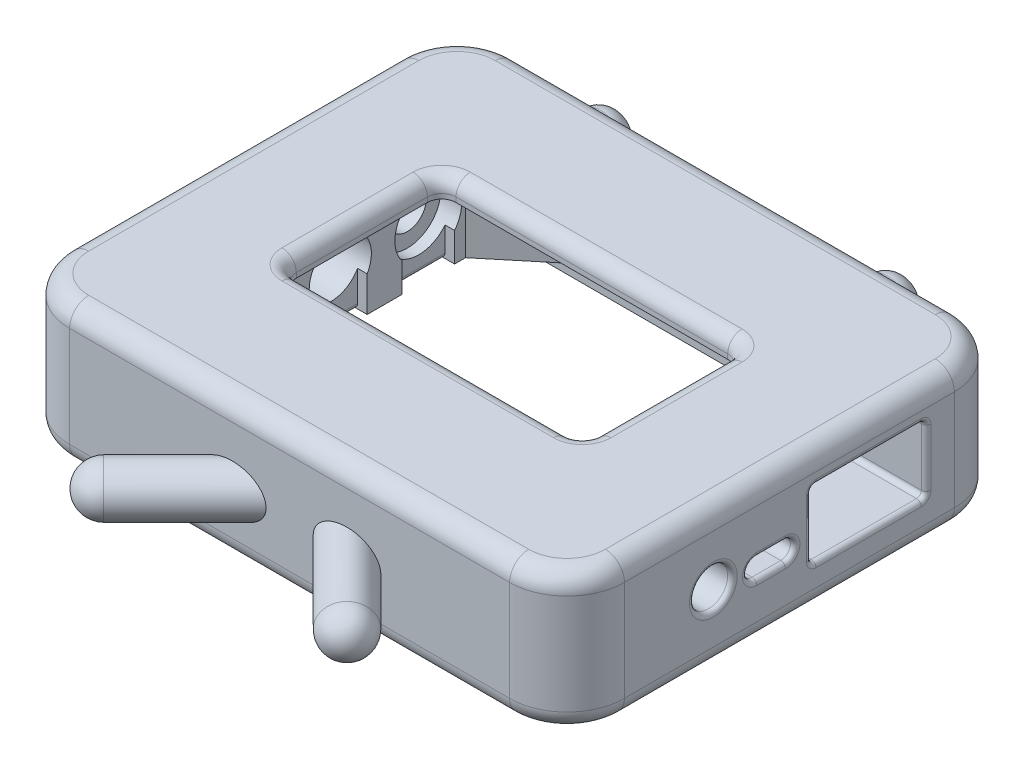
SolidWorks part; units mm, degrees
ref_plane "前视基准面" through (0, 0, 0) normal (0, 0, 1) x (1, 0, 0)
ref_plane "上视基准面" through (0, 0, 0) normal (0, 1, 0) x (1, 0, 0)
ref_plane "右视基准面" through (0, 0, 0) normal (1, 0, 0) x (0, 0, -1)
sketch "草图1" plane through (0, 0, 0) normal (0, 1, 0) x (1, 0, 0)
  line L0 (0, -23.25) -> (0, 24.5) construction
  line L7 (-29, 23.25) -> (29, 23.25)
  line L8 (-29, 23.25) -> (-29, -23.25)
  line L9 (-29, -23.25) -> (29, -23.25)
  line L10 (29, 23.25) -> (29, -23.25)
  line L11 (-29, 23.25) -> (29, -23.25) construction
  line L12 (-29, -23.25) -> (29, 23.25) construction
  line L13 (-29, 23.25) -> (29, 23.25) construction
  line L20 (-19.2, -17.25) -> (19.2, -17.25)
  line L21 (-19.2, -17.25) -> (-19.2, 20.15)
  line L22 (-19.2, 20.15) -> (19.2, 20.15)
  line L23 (19.2, -17.25) -> (19.2, 20.15)
  line L24 (-19.2, -17.25) -> (19.2, 20.15) construction
  line L25 (-19.2, 20.15) -> (19.2, -17.25) construction
  point P0 (0, 0)
  point P3 (0, 1.45)
  point P6 (0, 0)
  dimension "D1" = 58
  dimension "D2" = 46.5
  dimension "D3" = 6
  dimension "D4" = 38.4
  dimension "D5" = 37.4
  dimension "D6" = 3.1
extrude "凸台-拉伸1" add sketch "草图1" along normal blind 12.5
sketch "草图2" plane through (0, 12.5, 0) normal (0, 1, 0) x (1, 0, 0)
  line L13 (15.7, -8.35) -> (-15.7, -8.35)
  line L18 (15.7, -8.35) -> (15.7, 8.35)
  line L19 (15.7, 8.35) -> (-15.7, 8.35)
  line L20 (-15.7, -8.35) -> (-15.7, 8.35)
  line L25 (15.7, -8.35) -> (-15.7, 8.35) construction
  line L39 (15.7, 8.35) -> (-15.7, -8.35) construction
  line L40 (29, -23.25) -> (-29, -23.25)
  line L41 (29, -23.25) -> (29, 23.25)
  line L42 (29, 23.25) -> (-29, 23.25)
  line L43 (-29, -23.25) -> (-29, 23.25)
  line L44 (29, -23.25) -> (-29, 23.25) construction
  line L45 (29, 23.25) -> (-29, -23.25) construction
  point P0 (0, 0)
  point P4 (0, 0)
  dimension "D1" = 31.4
  dimension "D2" = 16.7
extrude "凸台-拉伸2" add sketch "草图2" along normal blind 2
fillet "圆角1" radius 6 4 edges at (29, 7.25, 23.25) (29, 7.25, -23.25) (-29, 7.25, -23.25) (-29, 7.25, 23.25)
sketch "草图11" plane through (0, 0, 23.25) normal (0, 0, 1) x (1, 0, 0)
  line L0 (0, 14.5) -> (0, 0)
  line L2 (-6, 13) -> (-6, 0) construction
  line L3 (-23, 0) -> (23, 0) construction
  line L4 (6, 13) -> (6, 0) construction
  line L6 (-23, 14.5) -> (23, 14.5) construction
  dimension "D1" = 6
  dimension "D2" = 6
ref_plane "left" through (14.625, 0, 14.625) normal (0.7071, 0, 0.7071) x (0, -1, 0)
ref_plane "right" through (-14.625, 0, 14.625) normal (-0.7071, 0, 0.7071) x (0, -1, 0)
sketch "草图8" plane through (-14.625, 0, 14.625) normal (-0.7071, 0, 0.7071) x (0, -1, 0)
  line L0 (-13, 12.1976) -> (0, 12.1976) construction
  circle A0 centre (-6.5, 12.1976) radius 2.5
  dimension "D1" = 5
extrude "凸台-拉伸3" add sketch "草图8" along normal blind 12 and the other way blind 3
sketch "草图9" plane through (14.625, 0, 14.625) normal (0.7071, 0, 0.7071) x (0, -1, 0)
  line L0 (-13, -12.1976) -> (0, -12.1976) construction
  circle A0 centre (-6.5, -12.1976) radius 2.5
  dimension "D1" = 5
extrude "凸台-拉伸4" add sketch "草图9" along normal blind 12 and the other way blind 3
fillet "圆角8" radius 2.5 2 edges at (-12.7175, 6.5, 33.503) (16.253, 6.5, 29.9675)
fillet "圆角10" radius 2 8 edges at (-27.2426, 0, -21.4926) (27.2426, 0, -21.4926) (29, 0, 0) (27.2426, 0, 21.4926) (-27.2426, 0, 21.4926) (-29, 0, 0) (0, 0, 23.25) (0, 0, -23.25)
fillet "圆角11" radius 1.5 8 edges at (15.7, 14.5, 0) (0, 14.5, -8.35) (-15.7, 14.5, 0) (0, 14.5, 8.35) (-15.7, 13.5, 8.35) (15.7, 13.5, 8.35) (15.7, 13.5, -8.35) (-15.7, 13.5, -8.35)
fillet "圆角12" radius 2 8 edges at (27.2426, 14.5, 21.4926) (0, 14.5, 23.25) (-27.2426, 14.5, 21.4926) (-29, 14.5, 0) (-27.2426, 14.5, -21.4926) (0, 14.5, -23.25) (27.2426, 14.5, -21.4926) (29, 14.5, 0)
sketch "草图12" plane through (0, 0, 0) normal (0, -1, 0) x (1, 0, 0)
  line L0 (-19.2, 17.25) -> (19.2, 17.25) construction
  line L1 (-25, 17.25) -> (25, 17.25)
  line L2 (-25, 17.25) -> (-25, -20.15)
  line L3 (-25, -20.15) -> (25, -20.15)
  line L4 (25, 17.25) -> (25, -20.15)
  line L5 (19.2, -20.15) -> (-19.2, -20.15) construction
  point P9 (0, 17.25)
  dimension "D1" = 50
  dimension "D2" = 37.4
extrude "切除-拉伸1" cut sketch "草图12" against normal blind 2
fillet "圆角13" radius 5 4 edges at (25, 1, 17.25) (25, 1, -20.15) (-25, 1, -20.15) (-25, 1, 17.25)
sketch "草图14" plane through (0, 12.5, 0) normal (0, -1, 0) x (1, 0, 0)
  line L0 (0, -20.15) -> (0, 17.25) construction
  line L1 (19.2, -20.15) -> (-19.2, -20.15) construction
  line L2 (-19.2, 17.25) -> (19.2, 17.25) construction
  line L3 (19.2, -1.45) -> (-19.2, -1.45) construction
  line L4 (19.2, 17.25) -> (19.2, -20.15) construction
  line L5 (-19.2, -20.15) -> (-19.2, 17.25) construction
  line L6 (-12.2, 17.25) -> (-19.2, 11.45)
  line L7 (-19.2, 11.45) -> (-19.2, 17.25)
  line L8 (-19.2, 17.25) -> (-12.2, 17.25)
  line L9 (19.2, 17.25) -> (12.2, 17.25)
  line L10 (19.2, 11.45) -> (19.2, 17.25)
  line L11 (12.2, 17.25) -> (19.2, 11.45)
  line L12 (12.2, -20.15) -> (19.2, -14.35)
  line L13 (19.2, -14.35) -> (19.2, -20.15)
  line L14 (19.2, -20.15) -> (12.2, -20.15)
  line L15 (-19.2, -20.15) -> (-12.2, -20.15)
  line L16 (-19.2, -14.35) -> (-19.2, -20.15)
  line L17 (-12.2, -20.15) -> (-19.2, -14.35)
  dimension "D1" = 5.8
  dimension "D2" = 7
extrude "凸台-拉伸5" add sketch "草图14" along normal up to surface (10.5 mm away) up to face at (-21.7452, 2, -1.45)
sketch "草图16" plane through (-29, 0, 0) normal (-1, 0, 0) x (0, 0, 1)
  line L1 (17.25, 12.5) -> (-17.25, 12.5) construction
  line L3 (-17.25, 12.5) -> (-17.25, 2) construction
  circle A0 centre (-1.25, 7.32) radius 3.25
  dimension "D1" = 6.5
  dimension "D2" = 5.18
  dimension "D3" = 16
extrude "切除-拉伸3" cut sketch "草图16" against normal up to next
sketch "草图17" plane through (-29, 0, 0) normal (-1, 0, 0) x (0, 0, 1)
  line L0 (-1.25, 10.57) -> (-1.25, 4.07) construction
  line L1 (17.25, 12.5) -> (-17.25, 12.5) construction
  line L2 (17.25, 2) -> (17.25, 12.5) construction
  circle A0 centre (-1.25, 7.32) radius 3.25 construction
  circle A1 centre (7.95, 7.21) radius 2
  circle A2 centre (-10.45, 7.21) radius 2
  point P9 (-1.25, 7.32)
  dimension "D1" = 4
  dimension "D2" = 5.29
  dimension "D3" = 9.2
  dimension "D4" = 9.3
extrude "切除-拉伸4" cut sketch "草图17" against normal up to next
sketch "草图18" plane through (29, 0, 0) normal (1, 0, 0) x (0, 0, -1)
  line L0 (-17.25, 12.5) -> (-17.25, 2) construction
  line L1 (17.25, 12.5) -> (-17.25, 12.5) construction
  circle A0 centre (-7.95, 7.21) radius 2
  dimension "D1" = 4
  dimension "D2" = 9.3
  dimension "D3" = 5.29
extrude "切除-拉伸5" cut sketch "草图18" against normal up to next
sketch "草图19" plane through (29, 0, 0) normal (1, 0, 0) x (0, 0, -1)
  line L0 (-3.4, 6.81) -> (-0.4, 6.81) construction
  line L1 (-3.4, 7.81) -> (-0.4, 7.81)
  line L2 (-3.4, 5.81) -> (-0.4, 5.81)
  line L3 (17.25, 12.5) -> (-17.25, 12.5) construction
  line L4 (-17.25, 12.5) -> (-17.25, 2) construction
  arc A0 (-3.4, 7.81) -> (-3.4, 5.81) centre (-3.4, 6.81) ccw
  arc A1 (-0.4, 5.81) -> (-0.4, 7.81) centre (-0.4, 6.81) ccw
  point P2 (-1.9, 6.81)
  dimension "D4" = 3
  dimension "D1" = 2
  dimension "D2" = 5.69
  dimension "D3" = 15.35
extrude "切除-拉伸6" cut sketch "草图19" against normal up to next
sketch "草图20" plane through (29, 0, 0) normal (1, 0, 0) x (0, 0, -1)
  line L0 (-17.25, 12.5) -> (-17.25, 2) construction
  line L1 (2.29, 11.32) -> (14.29, 11.32)
  line L2 (2.29, 11.32) -> (2.29, 4.32)
  line L3 (2.29, 4.32) -> (14.29, 4.32)
  line L4 (14.29, 11.32) -> (14.29, 4.32)
  line L5 (2.29, 11.32) -> (14.29, 4.32) construction
  line L6 (2.29, 4.32) -> (14.29, 11.32) construction
  line L7 (17.25, 12.5) -> (-17.25, 12.5) construction
  point P0 (8.29, 7.82)
  dimension "D1" = 12
  dimension "D2" = 7
  dimension "D3" = 25.54
  dimension "D4" = 4.68
extrude "切除-拉伸7" cut sketch "草图20" against normal up to next
fillet "圆角14" radius 0.5 12 edges at (29, 6.81, 4.4) (29, 7.81, 1.9) (29, 6.81, -0.6) (-29, 7.21, -12.45) (-29, 7.21, 9.95) (-29, 7.32, 2) (29, 5.81, 1.9) (29, 7.21, 5.95) (24.1, 11.32, -14.29) (24.1, 4.32, -14.29) (24.1, 4.32, -2.29) (24.1, 11.32, -2.29)
fillet "圆角15" radius 0.5 8 edges at (29, 4.4664, -2.4364) (29, 7.82, -2.29) (29, 11.1736, -2.4364) (29, 11.32, -8.29) (29, 11.1736, -14.1436) (29, 7.82, -14.29) (29, 4.4664, -14.1436) (29, 4.32, -8.29)
sketch "草图21" plane through (19.2, 0, 0) normal (-1, 0, 0) x (0, 0, 1)
  circle A0 centre (7.95, 7.21) radius 3.5
  dimension "D1" = 7
extrude "切除-拉伸8" cut sketch "草图21" against normal blind 2.2
sketch "草图22" plane through (-19.2, 0, 0) normal (1, 0, 0) x (0, 0, -1)
  circle A0 centre (-7.95, 7.21) radius 3.5
  circle A1 centre (10.45, 7.21) radius 3.5
  dimension "D1" = 7
  dimension "D2" = 7
extrude "切除-拉伸9" cut sketch "草图22" against normal blind 2.2
sketch "草图23" plane through (-19.2, 0, 0) normal (1, 0, 0) x (0, 0, -1)
  line L0 (-11.45, 2) -> (14.35, 2) construction
  line L1 (-10.7, 12.42) -> (-5.2, 12.42) construction
  line L2 (-10.7, 12.42) -> (-10.7, 2) construction
  line L3 (-10.7, 2) -> (-5.2, 2)
  line L4 (-5.2, 12.42) -> (-5.2, 2) construction
  line L5 (-10.7, 12.42) -> (-5.2, 2) construction
  line L6 (-10.7, 2) -> (-5.2, 12.42) construction
  line L7 (-10.7, 2) -> (-10.7, 7.21)
  line L8 (-1.4419, 12.42) -> (4.0581, 12.42) construction
  line L9 (-1.4419, 12.42) -> (-1.4419, 2) construction
  line L10 (-1.4419, 2) -> (4.0581, 2)
  line L11 (4.0581, 12.42) -> (4.0581, 2) construction
  line L12 (-1.4419, 12.42) -> (4.0581, 2) construction
  line L13 (-1.4419, 2) -> (4.0581, 12.42) construction
  line L14 (7.7, 12.42) -> (13.2, 12.42) construction
  line L15 (7.7, 12.42) -> (7.7, 2) construction
  line L16 (7.7, 2) -> (13.2, 2)
  line L17 (13.2, 12.42) -> (13.2, 2) construction
  line L18 (7.7, 12.42) -> (13.2, 2) construction
  line L19 (7.7, 2) -> (13.2, 12.42) construction
  line L20 (-10.7, 7.21) -> (-5.2, 7.21)
  line L21 (-5.2, 7.21) -> (-5.2, 2)
  line L22 (-1.4419, 2) -> (-1.4419, 7.21)
  line L23 (-1.4419, 7.21) -> (4.0581, 7.21)
  line L24 (4.0581, 7.21) -> (4.0581, 2)
  line L25 (7.7, 2) -> (7.7, 7.21)
  line L26 (7.7, 7.21) -> (13.2, 7.21)
  line L27 (13.2, 7.21) -> (13.2, 2)
  point P0 (-7.95, 7.21)
  point P8 (1.25, 7.32)
  point P14 (10.45, 7.21)
  dimension "D1" = 5.5
extrude "切除-拉伸10" cut sketch "草图23" against normal blind 1
fillet "圆角16" radius 0.5 3 edges at (-20.2, 2, -10.45) (-20.2, 2, -1.3081) (-20.2, 2, 7.95)
sketch "草图24" plane through (0, 0, -23.25) normal (0, 0, -1) x (-1, 0, 0)
  line L0 (0, 12.5) -> (0, 2) construction
  line L1 (23, 12.5) -> (-23, 12.5) construction
  line L2 (-23, 2) -> (23, 2) construction
  line L3 (12.5, 10) -> (12.5, 0)
  line L10 (23, 0) -> (27, 0) construction
  line L23 (-17.5, 10) -> (-17.5, 0)
  line L24 (-17.5, 0) -> (-12.5, 0)
  line L25 (-12.5, 10) -> (-12.5, 0)
  line L26 (17.5, 0) -> (12.5, 0)
  line L33 (17.5, 10) -> (17.5, 0)
  arc A4 (12.5, 10) -> (17.5, 10) centre (15, 10) cw
  arc A5 (-12.5, 10) -> (-17.5, 10) centre (-15, 10) ccw
  point P17 (15, 12.5)
  point P20 (-15, 12.5)
  dimension "D1" = 15
  dimension "D2" = 5
extrude "凸台-拉伸6" add sketch "草图24" along normal blind 3 and the other way up to next
sketch "草图26" plane through (0, 2, 0) normal (0, -1, 0) x (1, 0, 0)
  line L0 (-25, -1.45) -> (25, -1.45) construction
  line L1 (-25, 12.25) -> (-25, -15.15) construction
  line L2 (25, -15.15) -> (25, 12.25) construction
  line L3 (0, -1.45) -> (0, -20.5649) construction
  circle A0 centre (-20, 14.55) radius 1.05
  circle A1 centre (20, 14.55) radius 1.05
  circle A2 centre (20, -17.45) radius 1.05
  circle A3 centre (-20, -17.45) radius 1.05
  point P6 (0, -1.45)
  dimension "D1" = 2.1
  dimension "D2" = 20
  dimension "D3" = 16
extrude "切除-拉伸11" cut sketch "草图26" against normal blind 8
fillet "圆角19" radius 0.5 4 edges at (-20, 2, -16.4) (20, 2, -18.5) (20, 2, 15.6) (-20, 2, 13.5)
fillet "圆角20" radius 2 12 edges at (12.5, 5, -26.25) (15, 12.5, -26.25) (17.5, 5, -26.25) (15, 0, -26.25) (-17.5, 5, -26.25) (-12.5, 5, -26.25) (17.5, 0, -23.75) (12.5, 0, -23.75) (-17.5, 0, -23.75) (-12.5, 0, -23.75) (-15, 0, -26.25) (-15, 12.5, -26.25)
